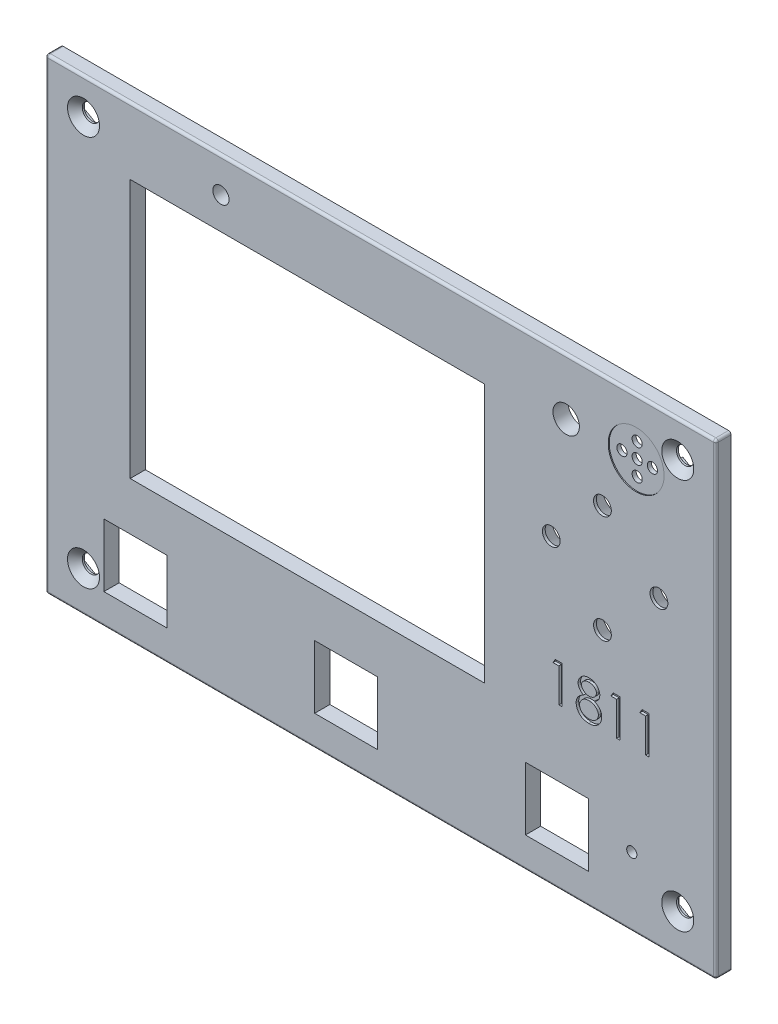
SolidWorks part; units mm, degrees
ref_plane "Plan de face" through (0, 0, 0) normal (0, 0, 1) x (1, 0, 0)
ref_plane "Plan de dessus" through (0, 0, 0) normal (0, 1, 0) x (1, 0, 0)
ref_plane "Plan de droite" through (0, 0, 0) normal (1, 0, 0) x (0, 0, -1)
sketch "Esquisse1" plane through (0, 0, 0) normal (0, 0, 1) x (1, 0, 0)
  line L1 (-52.1989, 55.8286) -> (79.8011, 55.8286)
  line L2 (-52.1989, 55.8286) -> (-52.1989, -36.1714)
  line L3 (-52.1989, -36.1714) -> (79.8011, -36.1714)
  line L4 (79.8011, 55.8286) -> (79.8011, -36.1714)
extrude "Boss.-Extru.1" add sketch "Esquisse1" along normal blind 3
sketch "Esquisse2" plane through (0, 0, 3) normal (0, 0, 1) x (1, 0, 0)
  line L0 (-52.1989, 55.8286) -> (-52.1989, -36.1714) construction
  line L1 (-35.5189, 42.7286) -> (34.2811, 42.7286)
  line L2 (-35.5189, 42.7286) -> (-35.5189, -8.2714)
  line L3 (-35.5189, -8.2714) -> (34.2811, -8.2714)
  line L4 (34.2811, 42.7286) -> (34.2811, -8.2714)
  line L5 (79.8011, 55.8286) -> (-52.1989, 55.8286) construction
  dimension "D1" = 16.68
  dimension "D2" = 13.1
extrude "Enlèv. mat.-Extru.1" cut sketch "Esquisse2" against normal blind 3
sketch "Esquisse3" plane through (0, 0, 3) normal (0, 0, 1) x (1, 0, 0)
  line L0 (-52.1989, 55.8286) -> (-52.1989, -36.1714) construction
  line L1 (-40.6889, -17.7414) -> (-28.2889, -17.7414)
  line L2 (-40.6889, -17.7414) -> (-40.6889, -30.1414)
  line L3 (-40.6889, -30.1414) -> (-28.2889, -30.1414)
  line L4 (-28.2889, -17.7414) -> (-28.2889, -30.1414)
  line L5 (-52.1989, -36.1714) -> (79.8011, -36.1714) construction
  dimension "D1" = 11.51
  dimension "D2" = 6.03
extrude "Enlèv. mat.-Extru.2" cut sketch "Esquisse3" against normal blind 3
sketch "Esquisse5" plane through (0, 0, 3) normal (0, 0, 1) x (1, 0, 0)
  line L1 (0.8111, -17.7414) -> (13.2111, -17.7414)
  line L2 (0.8111, -17.7414) -> (0.8111, -30.1414)
  line L3 (0.8111, -30.1414) -> (13.2111, -30.1414)
  line L4 (13.2111, -17.7414) -> (13.2111, -30.1414)
  line L5 (-52.1989, -36.1714) -> (79.8011, -36.1714) construction
  line L7 (-28.2889, -30.1414) -> (-28.2889, -17.7414) construction
  dimension "D1" = 29.1
  dimension "D2" = 6.03
extrude "Enlèv. mat.-Extru.3" cut sketch "Esquisse5" against normal blind 3
sketch "Esquisse6" plane through (0, 0, 3) normal (0, 0, 1) x (1, 0, 0)
  line L1 (42.3111, -17.7414) -> (54.7111, -17.7414)
  line L2 (42.3111, -17.7414) -> (42.3111, -30.1414)
  line L3 (42.3111, -30.1414) -> (54.7111, -30.1414)
  line L4 (54.7111, -17.7414) -> (54.7111, -30.1414)
  line L6 (-52.1989, -36.1714) -> (79.8011, -36.1714) construction
  line L7 (13.2111, -30.1414) -> (13.2111, -17.7414) construction
  dimension "D1" = 6.03
  dimension "D2" = 29.1
sketch "Esquisse7" plane through (0, 0, 3) normal (0, 0, 1) x (1, 0, 0)
  line L2 (79.8011, -36.1714) -> (79.8011, 55.8286) construction
  line L3 (79.8011, 55.8286) -> (-52.1989, 55.8286) construction
  circle A0 centre (57.4711, 12.3986) radius 1.75
  circle A1 centre (68.6011, 23.3686) radius 1.75
  circle A2 centre (57.4711, 33.5986) radius 1.75
  circle A3 centre (47.4011, 23.3686) radius 1.75
  dimension "D1" = 22.33
  dimension "D3" = 11.2
  dimension "D4" = 22.33
  dimension "D5" = 22.23
  dimension "D6" = 32.46
  dimension "D7" = 32.4
  dimension "D8" = 32.46
  dimension "D2" = 43.43
extrude "Enlèv. mat.-Extru.5" cut sketch "Esquisse7" against normal blind 3
extrude "Enlèv. mat.-Extru.6" cut sketch "Esquisse6" against normal blind 3 contours L2 L3 L4 L1
sketch "Esquisse8" plane through (0, 0, 3) normal (0, 0, 1) x (1, 0, 0)
  line L0 (79.8011, 55.8286) -> (-52.1989, 55.8286) construction
  line L1 (-52.1989, 55.8286) -> (-52.1989, -36.1714) construction
  circle A0 centre (-17.6489, 49.0186) radius 1.6
  dimension "D1" = 6.81
  dimension "D2" = 34.55
extrude "Enlèv. mat.-Extru.7" cut sketch "Esquisse8" against normal blind 3
sketch "Esquisse9" plane through (0, 0, 3) normal (0, 0, 1) x (1, 0, 0)
  line L1 (79.8011, 55.8286) -> (-52.1989, 55.8286) construction
  line L2 (79.8011, -36.1714) -> (79.8011, 55.8286) construction
  circle A0 centre (50.3311, 44.7686) radius 2.6
  dimension "D1" = 11.06
  dimension "D2" = 29.47
extrude "Enlèv. mat.-Extru.8" cut sketch "Esquisse9" against normal blind 3
sketch "Esquisse10" plane through (0, 0, 3) normal (0, 0, 1) x (1, 0, 0)
  line L0 (79.8011, 55.8286) -> (-52.1989, 55.8286) construction
  line L1 (79.8011, -36.1714) -> (79.8011, 55.8286) construction
  circle A0 centre (64.1111, 44.7686) radius 1
  circle A1 centre (64.1111, 47.7686) radius 1
  circle A2 centre (64.1111, 41.7686) radius 1
  circle A3 centre (61.1111, 44.7686) radius 1
  circle A4 centre (67.1111, 44.7686) radius 1
  dimension "D1" = 11.06
  dimension "D4" = 0
  dimension "D2" = 15.69
  dimension "D5" = 0
extrude "Enlèv. mat.-Extru.9" cut sketch "Esquisse10" against normal blind 3 and the other way through all
sketch "Esquisse12" plane through (0, 0, 3) normal (0, 0, 1) x (1, 0, 0)
  circle A2 centre (64.1111, 44.7686) radius 5
  circle A3 centre (64.1111, 44.7686) radius 5.5
extrude "Enlèv. mat.-Extru.10" cut sketch "Esquisse12" against normal blind 0.2 contours A3
sketch "Esquisse14" [suppressed] plane through (0, 0, 2) normal (0, 0, 1) x (1, 0, 0)
  circle A0 centre (64.1111, 44.7686) radius 5
fillet "Congé1" radius 0.5 1 edges at (-52.1989, 9.8286, 3)
fillet "Congé2" radius 0.5 3 edges at (-52.1989, -36.1714, 1.25) (-52.0524, -36.1714, 2.8536) (14.0511, -36.1714, 3)
fillet "Congé3" radius 0.5 3 edges at (79.8011, -36.1714, 1.25) (79.8011, -36.0249, 2.8536) (79.8011, 10.0786, 3)
fillet "Congé4" radius 0.5 5 edges at (79.8011, 55.8286, 1.25) (79.6547, 55.8286, 2.8536) (-52.1989, 55.8286, 1.25) (-52.0524, 55.8286, 2.8536) (13.8011, 55.8286, 3)
sketch "Esquisse15" plane through (0, 0, 3) normal (0, 0, 1) x (1, 0, 0)
  line L0 (-51.6989, 55.8286) -> (79.3011, 55.8286) construction
  line L1 (-52.1989, -35.6714) -> (-52.1989, 55.3286) construction
  line L2 (79.8011, 55.3286) -> (79.8011, -35.6714) construction
  line L3 (79.3011, -36.1714) -> (-51.6989, -36.1714) construction
  circle A0 centre (-44.6989, 48.8286) radius 1.7
  circle A1 centre (72.3011, 48.8286) radius 1.7
  circle A2 centre (-44.6989, -28.1714) radius 1.7
  circle A3 centre (72.3011, -28.1714) radius 1.7
  dimension "D1" = 7
  dimension "D3" = 7
  dimension "D5" = 7.5
  dimension "D7" = 8
  dimension "D2" = 7.5
  dimension "D4" = 7.5
  dimension "D6" = 8
  dimension "D8" = 7.5
extrude "Enlèv. mat.-Extru.11" cut sketch "Esquisse15" against normal blind 3
sketch "Esquisse20" plane through (0, 0, 3) normal (0, 0, 1) x (1, 0, 0)
  circle A0 centre (63.2511, -22.5834) radius 1
  circle A1 centre (-44.6989, -28.1714) radius 1.7 construction
  dimension "D1" = 107.95
  dimension "D2" = 5.588
extrude "Enlèv. mat.-Extru.12" cut sketch "Esquisse20" against normal blind 3
sketch "Esquisse23" plane through (0, 0, 0) normal (0, 0, -1) x (-1, 0, 0)
  circle A0 centre (-64.1111, 44.7686) radius 6.5
extrude "Enlèv. mat.-Extru.13" cut sketch "Esquisse23" against normal blind 2
sketch "Esquisse24" plane through (0, 0, 3) normal (0, 0, 1) x (1, 0, 0)
  text T0 "1811" font "Century Gothic" height in points 28
extrude "Enlèv. mat.-Extru.17" cut sketch "Esquisse24" against normal blind 0.5
sketch "Esquisse25" plane through (0, 0, 0) normal (0, 0, -1) x (-1, 0, 0)
  circle A0 centre (-47.4011, 23.3686) radius 3
  circle A1 centre (-47.4011, 23.3686) radius 1.75 construction
  dimension "D1" = 0
extrude "Enlèv. mat.-Extru.18" cut sketch "Esquisse25" against normal blind 3 draft 27
sketch "Esquisse26" plane through (0, 0, 0) normal (0, 0, -1) x (-1, 0, 0)
  circle A0 centre (-57.4711, 12.3986) radius 3
  circle A1 centre (-57.4711, 12.3986) radius 1.75 construction
  dimension "D1" = 0
extrude "Enlèv. mat.-Extru.19" cut sketch "Esquisse26" against normal blind 3 draft 27
sketch "Esquisse27" plane through (0, 0, 0) normal (0, 0, -1) x (-1, 0, 0)
  circle A0 centre (-68.6011, 23.3686) radius 3
  circle A1 centre (-68.6011, 23.3686) radius 1.75 construction
  dimension "D1" = 0
extrude "Enlèv. mat.-Extru.20" cut sketch "Esquisse27" against normal blind 3 draft 27
sketch "Esquisse28" plane through (0, 0, 0) normal (0, 0, -1) x (-1, 0, 0)
  circle A0 centre (-57.4711, 33.5986) radius 3
  circle A1 centre (-57.4711, 33.5986) radius 1.75 construction
  dimension "D1" = 0
extrude "Enlèv. mat.-Extru.21" cut sketch "Esquisse28" against normal blind 3 draft 27
hole_wizard "Fraisage pour vis à tête fraisée M32" positions "Esquisse31" profile "Esquisse32" countersink size "M3" standard "Ansi Metric" end condition through all
sketch "Esquisse31" plane through (0, 0, 3) normal (0, 0, 1) x (1, 0, 0)
  point P0 (-44.6989, 48.8286)
  point P3 (-44.6989, -28.1714)
  point P6 (72.3011, -28.1714)
  point P9 (72.3011, 48.8286)
sketch "Esquisse32" plane through (-44.6989, 48.8286, 3) normal (1, 0, 0) x (0, -1, 0)
  line L0 (0, 0) -> (0, 3)
  line L1 (0, 3) -> (1.7, 3)
  line L2 (1.7, 3) -> (1.7, 1.45)
  line L3 (1.7, 1.45) -> (3.15, 0)
  line L5 (3.15, 0) -> (0, 0)
  line L6 (-1.7, 1.45) -> (-3.15, 0) construction
  line L11 (0, -6.35) -> (0, 107.95) construction
  dimension "Diamètre du perçage jusqu'au prochain" = 3.4
  dimension "Profondeur du perçage jusqu'au prochain" = 3
  dimension "Diamètre du fraisage entrant" = 6.3
  dimension "Angle du fraisage entrant" = 90
sketch "Esquisse33" plane through (0, 0, 0) normal (0, 0, -1) x (-1, 0, 0)
  line L0 (52.1989, 55.3286) -> (52.1989, -35.6714) construction
  line L1 (44.6989, -24.9714) -> (41.9276, -26.5714)
  line L2 (41.9276, -26.5714) -> (41.9276, -29.7714)
  line L3 (41.9276, -29.7714) -> (44.6989, -31.3714)
  line L4 (44.6989, -31.3714) -> (47.4701, -29.7714)
  line L5 (47.4701, -29.7714) -> (47.4701, -26.5714)
  line L6 (47.4701, -26.5714) -> (44.6989, -24.9714)
  circle A0 centre (44.6989, -28.1714) radius 2.7713 construction
  circle A1 centre (44.6989, -28.1714) radius 1.7 construction
  dimension "D1" = 0
extrude "Enlèv. mat.-Extru.22" cut sketch "Esquisse33" against normal blind 1.2
sketch "Esquisse34" plane through (0, 0, 0) normal (0, 0, -1) x (-1, 0, 0)
  line L0 (52.1989, 55.3286) -> (52.1989, -35.6714) construction
  line L1 (44.6989, 52.0286) -> (41.9276, 50.4286)
  line L2 (41.9276, 50.4286) -> (41.9276, 47.2286)
  line L3 (41.9276, 47.2286) -> (44.6989, 45.6286)
  line L4 (44.6989, 45.6286) -> (47.4701, 47.2286)
  line L5 (47.4701, 47.2286) -> (47.4701, 50.4286)
  line L6 (47.4701, 50.4286) -> (44.6989, 52.0286)
  circle A0 centre (44.6989, 48.8286) radius 2.7713 construction
  circle A1 centre (44.6989, 48.8286) radius 1.7 construction
  dimension "D1" = 0
extrude "Enlèv. mat.-Extru.23" cut sketch "Esquisse34" against normal blind 1.2
sketch "Esquisse35" plane through (0, 0, 0) normal (0, 0, -1) x (-1, 0, 0)
  line L0 (-79.8011, -35.6714) -> (-79.8011, 55.3286) construction
  line L1 (-72.3011, 52.0286) -> (-75.0724, 50.4286)
  line L2 (-75.0724, 50.4286) -> (-75.0724, 47.2286)
  line L3 (-75.0724, 47.2286) -> (-72.3011, 45.6286)
  line L4 (-72.3011, 45.6286) -> (-69.5299, 47.2286)
  line L5 (-69.5299, 47.2286) -> (-69.5299, 50.4286)
  line L6 (-69.5299, 50.4286) -> (-72.3011, 52.0286)
  circle A0 centre (-72.3011, 48.8286) radius 2.7713 construction
  circle A1 centre (-72.3011, 48.8286) radius 1.7 construction
  dimension "D1" = 0
extrude "Enlèv. mat.-Extru.24" cut sketch "Esquisse35" against normal blind 1.2
sketch "Esquisse36" plane through (0, 0, 0) normal (0, 0, -1) x (-1, 0, 0)
  line L0 (-79.8011, -35.6714) -> (-79.8011, 55.3286) construction
  line L1 (-72.3011, -24.9714) -> (-75.0724, -26.5714)
  line L2 (-75.0724, -26.5714) -> (-75.0724, -29.7714)
  line L3 (-75.0724, -29.7714) -> (-72.3011, -31.3714)
  line L4 (-72.3011, -31.3714) -> (-69.5299, -29.7714)
  line L5 (-69.5299, -29.7714) -> (-69.5299, -26.5714)
  line L6 (-69.5299, -26.5714) -> (-72.3011, -24.9714)
  circle A0 centre (-72.3011, -28.1714) radius 2.7713 construction
  circle A1 centre (-72.3011, -28.1714) radius 1.7 construction
  dimension "D1" = 0
extrude "Enlèv. mat.-Extru.25" cut sketch "Esquisse36" against normal blind 1.2
